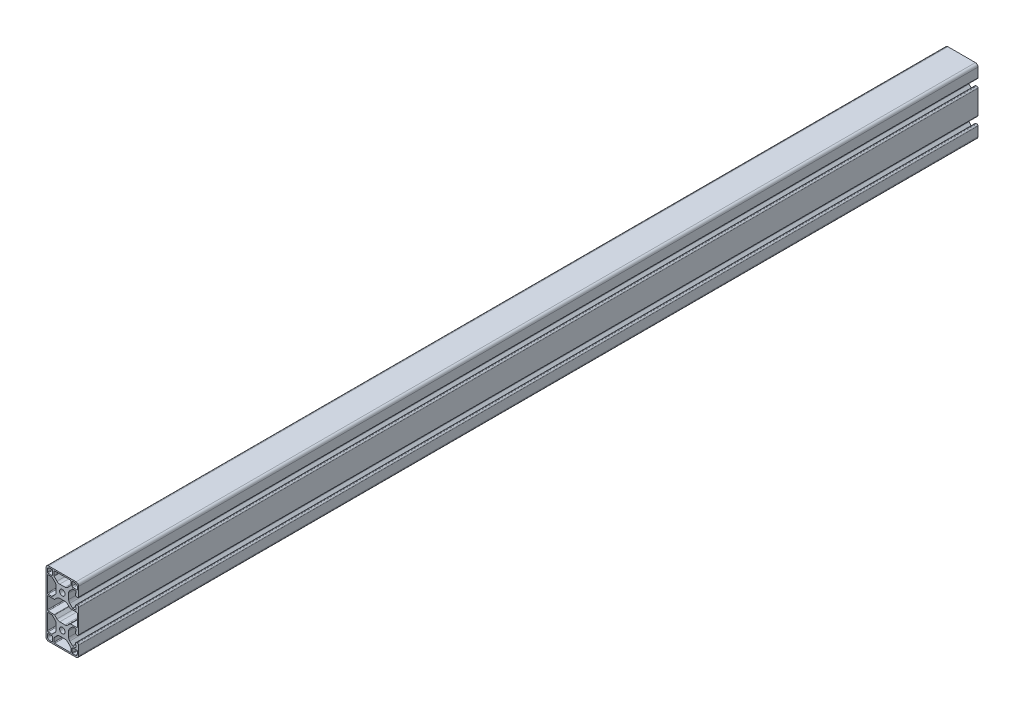
SolidWorks part; units mm, degrees
ref_plane "Front Plane" through (0, 0, 0) normal (0, 0, 1) x (1, 0, 0)
ref_plane "Top Plane" through (0, 0, 0) normal (0, 1, 0) x (1, 0, 0)
ref_plane "Right Plane" through (0, 0, 0) normal (1, 0, 0) x (0, 0, -1)
ref_plane "Plane1" through (0, 0, -4000) normal (0, 0, -1) x (-1, 0, 0)
sketch "Sketch1" plane through (0, 0, -4000) normal (0, 0, -1) x (-1, 0, 0)
  line L0 (18.3499, 55.5501) -> (18.3499, 52.5701)
  line L1 (17.7199, 51.9401) -> (13.2099, 51.9401)
  line L2 (11.9399, 53.2101) -> (11.9399, 57.7201)
  line L3 (12.5699, 58.3501) -> (15.5499, 58.3501)
  line L4 (18.3499, -12.5701) -> (18.3499, -15.5501)
  line L5 (15.5499, -18.3501) -> (12.5699, -18.3501)
  line L6 (11.9399, -17.7201) -> (11.9399, -13.2101)
  line L7 (13.2099, -11.9401) -> (17.7199, -11.9401)
  line L8 (18.3492, 27.1761) -> (18.3492, 12.8239)
  line L9 (17.4603, 11.935) -> (9.9702, 11.935)
  line L10 (9.3409, 11.6743) -> (6.5812, 8.9146)
  line L11 (3.2224, 7.5234) -> (-3.2224, 7.5234)
  line L12 (-6.5812, 8.9146) -> (-9.3409, 11.6743)
  line L13 (-9.9702, 11.935) -> (-17.4603, 11.935)
  line L14 (-18.3492, 12.8239) -> (-18.3492, 27.1761)
  line L15 (-17.4603, 28.065) -> (-9.9702, 28.065)
  line L16 (-9.3409, 28.3257) -> (-6.5812, 31.0854)
  line L17 (-3.2224, 32.4766) -> (3.2224, 32.4766)
  line L18 (6.5812, 31.0854) -> (9.3409, 28.3257)
  line L19 (9.9702, 28.065) -> (17.4603, 28.065)
  line L20 (18.3492, 9.3961) -> (18.3492, -9.3961)
  line L21 (17.4603, -10.285) -> (12.9871, -10.285)
  line L22 (12.3578, -10.0243) -> (9.0912, -6.7578)
  line L23 (7.7, -3.399) -> (7.7, 3.399)
  line L24 (9.0912, 6.7578) -> (12.3578, 10.0243)
  line L25 (12.9871, 10.285) -> (17.4603, 10.285)
  line L26 (18.3492, 49.3961) -> (18.3492, 30.6039)
  line L27 (17.4603, 29.715) -> (12.9871, 29.715)
  line L28 (12.3578, 29.9757) -> (9.0912, 33.2422)
  line L29 (7.7, 36.601) -> (7.7, 43.399)
  line L30 (9.0912, 46.7578) -> (12.3578, 50.0243)
  line L31 (12.9871, 50.285) -> (17.4603, 50.285)
  line L32 (10.2899, 57.4612) -> (10.2899, 52.992)
  line L33 (10.0292, 52.3627) -> (6.5812, 48.9146)
  line L34 (3.2224, 47.5234) -> (-3.2224, 47.5234)
  line L35 (-6.5812, 48.9146) -> (-10.0292, 52.3627)
  line L36 (-10.2899, 52.992) -> (-10.2899, 57.4612)
  line L37 (-9.401, 58.3501) -> (9.401, 58.3501)
  line L38 (10.2899, -12.992) -> (10.2899, -17.4216)
  line L39 (9.401, -18.3105) -> (-9.401, -18.3105)
  line L40 (-10.2899, -17.4216) -> (-10.2899, -12.992)
  line L41 (-10.0292, -12.3627) -> (-6.5812, -8.9146)
  line L42 (-3.2224, -7.5234) -> (3.2224, -7.5234)
  line L43 (6.5812, -8.9146) -> (10.0292, -12.3627)
  line L44 (-11.9399, 57.7201) -> (-11.9399, 53.2101)
  line L45 (-13.2099, 51.9401) -> (-17.7199, 51.9401)
  line L46 (-18.3499, 52.5701) -> (-18.3499, 55.5501)
  line L47 (-15.5499, 58.3501) -> (-12.5699, 58.3501)
  line L48 (-11.9399, -13.2101) -> (-11.9399, -17.7201)
  line L49 (-12.5699, -18.3501) -> (-15.5499, -18.3501)
  line L50 (-18.3499, -15.5501) -> (-18.3499, -12.5701)
  line L51 (-17.7199, -11.9401) -> (-13.2099, -11.9401)
  line L52 (20, -16.83) -> (20, 56.83)
  line L53 (16.83, 60) -> (-16.83, 60)
  line L54 (-20, 56.83) -> (-20, 45.5403)
  line L55 (-18.5197, 44.06) -> (-17.8048, 44.06)
  line L56 (-15.94, 45.9248) -> (-15.94, 47.2807)
  line L57 (-15.94, 47.2807) -> (-16.7, 47.2807)
  line L58 (-16.7, 47.2807) -> (-16.7, 48.9483)
  line L59 (-15.3633, 50.285) -> (-12.9871, 50.285)
  line L60 (-12.3578, 50.0243) -> (-9.0912, 46.7578)
  line L61 (-7.7, 43.399) -> (-7.7, 36.601)
  line L62 (-9.0912, 33.2422) -> (-12.3578, 29.9757)
  line L63 (-12.9871, 29.715) -> (-15.3633, 29.715)
  line L64 (-16.7, 31.0517) -> (-16.7, 32.7193)
  line L65 (-16.7, 32.7193) -> (-15.94, 32.7193)
  line L66 (-15.94, 32.7193) -> (-15.94, 34.0752)
  line L67 (-17.8048, 35.94) -> (-18.5197, 35.94)
  line L68 (-20, 34.4597) -> (-20, 5.5403)
  line L69 (-18.5197, 4.06) -> (-17.8048, 4.06)
  line L70 (-15.94, 5.9248) -> (-15.94, 7.2807)
  line L71 (-15.94, 7.2807) -> (-16.7, 7.2807)
  line L72 (-16.7, 7.2807) -> (-16.7, 9.015)
  line L73 (-15.43, 10.285) -> (-12.9871, 10.285)
  line L74 (-12.3578, 10.0243) -> (-9.0912, 6.7578)
  line L75 (-7.7, 3.399) -> (-7.7, -3.399)
  line L76 (-9.0912, -6.7578) -> (-12.3578, -10.0243)
  line L77 (-12.9871, -10.285) -> (-15.3633, -10.285)
  line L78 (-16.7, -8.9483) -> (-16.7, -7.2807)
  line L79 (-16.7, -7.2807) -> (-15.94, -7.2807)
  line L80 (-15.94, -7.2807) -> (-15.94, -5.9248)
  line L81 (-17.8048, -4.06) -> (-18.5197, -4.06)
  line L82 (-20, -5.5403) -> (-20, -16.83)
  line L83 (-16.83, -20) -> (16.83, -20)
  arc A0 (15.5499, 58.3501) -> (18.3499, 55.5501) centre (15.5499, 55.5501) cw
  arc A1 (18.3499, 52.5701) -> (17.7199, 51.9401) centre (17.7199, 52.5701) cw
  arc A2 (13.2099, 51.9401) -> (11.9399, 53.2101) centre (13.2099, 53.2101) cw
  arc A3 (11.9399, 57.7201) -> (12.5699, 58.3501) centre (12.5699, 57.7201) cw
  arc A4 (18.3499, -15.5501) -> (15.5499, -18.3501) centre (15.5499, -15.5501) cw
  arc A5 (12.5699, -18.3501) -> (11.9399, -17.7201) centre (12.5699, -17.7201) cw
  arc A6 (11.9399, -13.2101) -> (13.2099, -11.9401) centre (13.2099, -13.2101) cw
  arc A7 (17.7199, -11.9401) -> (18.3499, -12.5701) centre (17.7199, -12.5701) cw
  arc A8 (18.3492, 12.8239) -> (17.4603, 11.935) centre (17.4603, 12.8239) cw
  arc A9 (9.9702, 11.935) -> (9.3409, 11.6743) centre (9.9702, 11.045) ccw
  arc A10 (6.5812, 8.9146) -> (3.2224, 7.5234) centre (3.2224, 12.2734) cw
  arc A11 (-3.2224, 7.5234) -> (-6.5812, 8.9146) centre (-3.2224, 12.2734) cw
  arc A12 (-9.3409, 11.6743) -> (-9.9702, 11.935) centre (-9.9702, 11.045) ccw
  arc A13 (-17.4603, 11.935) -> (-18.3492, 12.8239) centre (-17.4603, 12.8239) cw
  arc A14 (-18.3492, 27.1761) -> (-17.4603, 28.065) centre (-17.4603, 27.1761) cw
  arc A15 (-9.9702, 28.065) -> (-9.3409, 28.3257) centre (-9.9702, 28.955) ccw
  arc A16 (-6.5812, 31.0854) -> (-3.2224, 32.4766) centre (-3.2224, 27.7266) cw
  arc A17 (3.2224, 32.4766) -> (6.5812, 31.0854) centre (3.2224, 27.7266) cw
  arc A18 (9.3409, 28.3257) -> (9.9702, 28.065) centre (9.9702, 28.955) ccw
  arc A19 (17.4603, 28.065) -> (18.3492, 27.1761) centre (17.4603, 27.1761) cw
  arc A20 (18.3492, -9.3961) -> (17.4603, -10.285) centre (17.4603, -9.3961) cw
  arc A21 (12.9871, -10.285) -> (12.3578, -10.0243) centre (12.9871, -9.395) cw
  arc A22 (9.0912, -6.7578) -> (7.7, -3.399) centre (12.45, -3.399) cw
  arc A23 (7.7, 3.399) -> (9.0912, 6.7578) centre (12.45, 3.399) cw
  arc A24 (12.3578, 10.0243) -> (12.9871, 10.285) centre (12.9871, 9.395) cw
  arc A25 (17.4603, 10.285) -> (18.3492, 9.3961) centre (17.4603, 9.3961) cw
  arc A26 (18.3492, 30.6039) -> (17.4603, 29.715) centre (17.4603, 30.6039) cw
  arc A27 (12.9871, 29.715) -> (12.3578, 29.9757) centre (12.9871, 30.605) cw
  arc A28 (9.0912, 33.2422) -> (7.7, 36.601) centre (12.45, 36.601) cw
  arc A29 (7.7, 43.399) -> (9.0912, 46.7578) centre (12.45, 43.399) cw
  arc A30 (12.3578, 50.0243) -> (12.9871, 50.285) centre (12.9871, 49.395) cw
  arc A31 (17.4603, 50.285) -> (18.3492, 49.3961) centre (17.4603, 49.3961) cw
  arc A32 (10.2899, 52.992) -> (10.0292, 52.3627) centre (9.3999, 52.992) cw
  arc A33 (6.5812, 48.9146) -> (3.2224, 47.5234) centre (3.2224, 52.2734) cw
  arc A34 (-3.2224, 47.5234) -> (-6.5812, 48.9146) centre (-3.2224, 52.2734) cw
  arc A35 (-10.0292, 52.3627) -> (-10.2899, 52.992) centre (-9.3999, 52.992) cw
  arc A36 (-10.2899, 57.4612) -> (-9.401, 58.3501) centre (-9.401, 57.4612) cw
  arc A37 (9.401, 58.3501) -> (10.2899, 57.4612) centre (9.401, 57.4612) cw
  arc A38 (10.0292, -12.3627) -> (10.2899, -12.992) centre (9.3999, -12.992) cw
  arc A39 (10.2899, -17.4216) -> (9.401, -18.3105) centre (9.401, -17.4216) cw
  arc A40 (-9.401, -18.3105) -> (-10.2899, -17.4216) centre (-9.401, -17.4216) cw
  arc A41 (-10.2899, -12.992) -> (-10.0292, -12.3627) centre (-9.3999, -12.992) cw
  arc A42 (-6.5812, -8.9146) -> (-3.2224, -7.5234) centre (-3.2224, -12.2734) cw
  arc A43 (3.2224, -7.5234) -> (6.5812, -8.9146) centre (3.2224, -12.2734) cw
  circle A44 centre (0, 40) radius 3.405
  circle A45 centre (0, 0) radius 3.405
  arc A46 (-11.9399, 53.2101) -> (-13.2099, 51.9401) centre (-13.2099, 53.2101) cw
  arc A47 (-17.7199, 51.9401) -> (-18.3499, 52.5701) centre (-17.7199, 52.5701) cw
  arc A48 (-18.3499, 55.5501) -> (-15.5499, 58.3501) centre (-15.5499, 55.5501) cw
  arc A49 (-12.5699, 58.3501) -> (-11.9399, 57.7201) centre (-12.5699, 57.7201) cw
  arc A50 (-13.2099, -11.9401) -> (-11.9399, -13.2101) centre (-13.2099, -13.2101) cw
  arc A51 (-11.9399, -17.7201) -> (-12.5699, -18.3501) centre (-12.5699, -17.7201) cw
  arc A52 (-15.5499, -18.3501) -> (-18.3499, -15.5501) centre (-15.5499, -15.5501) cw
  arc A53 (-18.3499, -12.5701) -> (-17.7199, -11.9401) centre (-17.7199, -12.5701) cw
  arc A54 (20, 56.83) -> (16.83, 60) centre (16.83, 56.83) ccw
  arc A55 (-16.83, 60) -> (-20, 56.83) centre (-16.83, 56.83) ccw
  arc A56 (-20, 45.5403) -> (-18.5197, 44.06) centre (-18.5197, 45.5403) ccw
  arc A57 (-17.8048, 44.06) -> (-15.94, 45.9248) centre (-17.8048, 45.9248) ccw
  arc A58 (-16.7, 48.9483) -> (-15.3633, 50.285) centre (-15.3633, 48.9483) cw
  arc A59 (-12.9871, 50.285) -> (-12.3578, 50.0243) centre (-12.9871, 49.395) cw
  arc A60 (-9.0912, 46.7578) -> (-7.7, 43.399) centre (-12.45, 43.399) cw
  arc A61 (-7.7, 36.601) -> (-9.0912, 33.2422) centre (-12.45, 36.601) cw
  arc A62 (-12.3578, 29.9757) -> (-12.9871, 29.715) centre (-12.9871, 30.605) cw
  arc A63 (-15.3633, 29.715) -> (-16.7, 31.0517) centre (-15.3633, 31.0517) cw
  arc A64 (-15.94, 34.0752) -> (-17.8048, 35.94) centre (-17.8048, 34.0752) ccw
  arc A65 (-18.5197, 35.94) -> (-20, 34.4597) centre (-18.5197, 34.4597) ccw
  arc A66 (-20, 5.5403) -> (-18.5197, 4.06) centre (-18.5197, 5.5403) ccw
  arc A67 (-17.8048, 4.06) -> (-15.94, 5.9248) centre (-17.8048, 5.9248) ccw
  arc A68 (-16.7, 9.015) -> (-15.43, 10.285) centre (-15.43, 9.015) cw
  arc A69 (-12.9871, 10.285) -> (-12.3578, 10.0243) centre (-12.9871, 9.395) cw
  arc A70 (-9.0912, 6.7578) -> (-7.7, 3.399) centre (-12.45, 3.399) cw
  arc A71 (-7.7, -3.399) -> (-9.0912, -6.7578) centre (-12.45, -3.399) cw
  arc A72 (-12.3578, -10.0243) -> (-12.9871, -10.285) centre (-12.9871, -9.395) cw
  arc A73 (-15.3633, -10.285) -> (-16.7, -8.9483) centre (-15.3633, -8.9483) cw
  arc A74 (-15.94, -5.9248) -> (-17.8048, -4.06) centre (-17.8048, -5.9248) ccw
  arc A75 (-18.5197, -4.06) -> (-20, -5.5403) centre (-18.5197, -5.5403) ccw
  arc A76 (-20, -16.83) -> (-16.83, -20) centre (-16.83, -16.83) ccw
  arc A77 (16.83, -20) -> (20, -16.83) centre (16.83, -16.83) ccw
extrude "Boss-Extrude1" add sketch "Sketch1" against normal blind 1100
